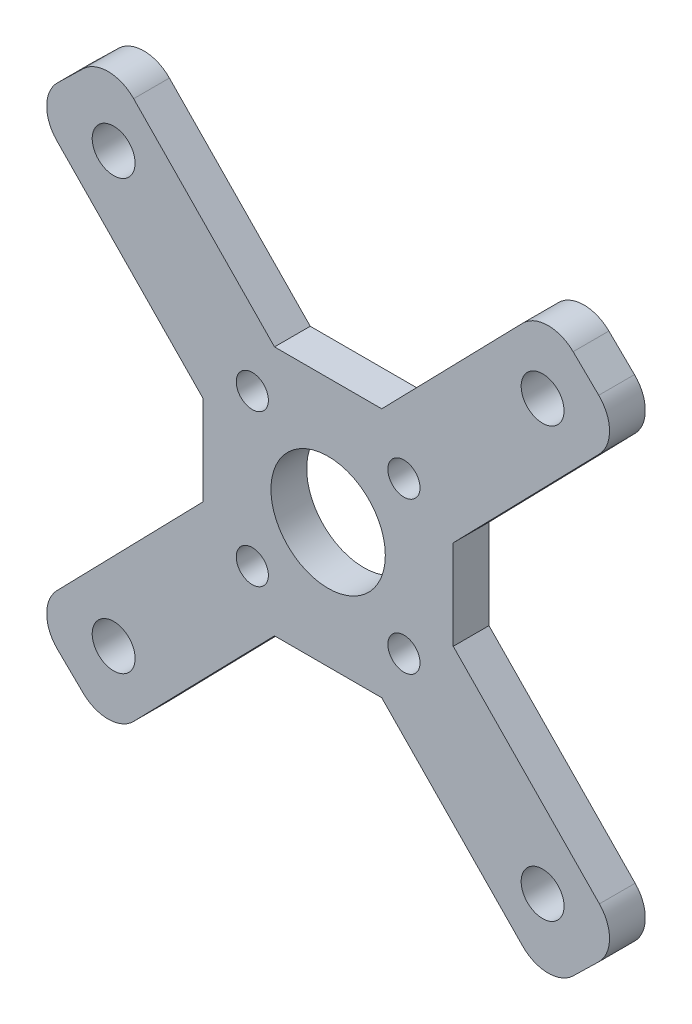
SolidWorks part; units mm, degrees
ref_plane "Plan de face" through (0, 0, 0) normal (0, 0, 1) x (1, 0, 0)
ref_plane "Plan de dessus" through (0, 0, 0) normal (0, 1, 0) x (1, 0, 0)
ref_plane "Plan de droite" through (0, 0, 0) normal (1, 0, 0) x (0, 0, -1)
sketch "Esquisse1" plane through (0, 0, 0) normal (0, 0, 1) x (1, 0, 0)
  line L0 (-10.605, 10.605) -> (-10.605, -10.605) construction
  line L1 (7.5, -17.5) -> (-7.5, -17.5)
  line L2 (17.5, -7.5) -> (17.5, 7.5)
  line L3 (7.5, 17.5) -> (-7.5, 17.5)
  line L4 (-17.5, -7.5) -> (-17.5, 7.5)
  line L5 (17.5, -17.5) -> (-17.5, 17.5) construction
  line L6 (17.5, 17.5) -> (-17.5, -17.5) construction
  line L7 (-10.605, 10.605) -> (10.605, 10.605) construction
  line L8 (10.605, 10.605) -> (10.605, -10.605) construction
  circle A0 centre (0, 0) radius 8
  circle A1 centre (-10.605, 10.605) radius 2.25
  circle A2 centre (10.605, 10.605) radius 2.25
  circle A3 centre (-10.605, -10.605) radius 2.25
  circle A4 centre (10.605, -10.605) radius 2.25
  arc A5 (-7.5, -17.5) -> (-17.5, -7.5) centre (-7.5, -7.5) cw
  arc A6 (7.5, -17.5) -> (17.5, -7.5) centre (7.5, -7.5) ccw
  arc A7 (17.5, 7.5) -> (7.5, 17.5) centre (7.5, 7.5) ccw
  arc A8 (-7.5, 17.5) -> (-17.5, 7.5) centre (-7.5, 7.5) ccw
  point P0 (0, 0)
  point P16 (0, 0)
  point P17 (8.9507, -11.9448)
  point P18 (10.605, 0)
  point P19 (0, 10.605)
  point P20 (-10.605, 0)
  point P21 (0, 0)
  point P22 (9.4172, 10.605)
  dimension "D1" = 4.5
  dimension "D2" = 4.5
  dimension "D3" = 4.5
  dimension "D4" = 4.5
  dimension "D7" = 16
  dimension "D10" = 10
  dimension "D5" = 21.21
  dimension "D6" = 21.21
  dimension "D8" = 35
  dimension "D9" = 35
extrude "Boss.-Extru.1" add sketch "Esquisse1" along normal blind 5
sketch "Esquisse2" plane through (0, 0, 5) normal (0, 0, 1) x (1, 0, 0)
  line L0 (-38.0784, 38.0784) -> (30.6138, -30.6138) construction
  line L1 (37.8813, 37.8813) -> (-34.8497, -34.8497) construction
  line L2 (-17.4124, 6.1793) -> (-37.9445, 27.2476)
  line L3 (-37.8534, 34.3181) -> (-34.2726, 37.8078)
  line L4 (-27.2021, 37.7167) -> (-7.5, 17.5)
  line L5 (-30, 30) -> (-42.1259, 42.1259) construction
  line L6 (0, 38.0784) -> (0, -34.8497) construction
  line L7 (-51.3686, 0) -> (60.5572, 0) construction
  line L8 (37.8534, 34.3181) -> (34.2726, 37.8078)
  line L9 (17.4124, 6.1793) -> (37.9445, 27.2476)
  line L10 (27.2021, 37.7167) -> (7.5, 17.5)
  line L11 (17.4124, -6.1793) -> (37.9445, -27.2476)
  line L12 (27.2021, -37.7167) -> (7.5, -17.5)
  line L13 (37.8534, -34.3181) -> (34.2726, -37.8078)
  line L14 (-37.8534, -34.3181) -> (-34.2726, -37.8078)
  line L15 (-17.4124, -6.1793) -> (-37.9445, -27.2476)
  line L16 (-27.2021, -37.7167) -> (-7.5, -17.5)
  circle A0 centre (-10.605, -10.605) radius 2.25 construction
  circle A1 centre (10.605, -10.605) radius 2.25 construction
  circle A2 centre (10.605, 10.605) radius 2.25 construction
  circle A3 centre (-10.605, 10.605) radius 2.25 construction
  circle A4 centre (-10.605, -10.605) radius 2.25
  circle A5 centre (10.605, -10.605) radius 2.25
  circle A6 centre (10.605, 10.605) radius 2.25
  circle A7 centre (-10.605, 10.605) radius 2.25
  circle A8 centre (-30, 30) radius 3
  circle A9 centre (30, 30) radius 3
  circle A10 centre (-30, -30) radius 3
  circle A11 centre (30, -30) radius 3
  arc A12 (-7.5, 17.5) -> (-17.5, 7.5) centre (-7.5, 7.5) ccw construction
  arc A13 (-7.5, 17.5) -> (-17.4124, 6.1793) centre (-7.5, 7.5) ccw
  arc A14 (7.5, 17.5) -> (17.4124, 6.1793) centre (7.5, 7.5) cw
  arc A15 (7.5, -17.5) -> (17.4124, -6.1793) centre (7.5, -7.5) ccw
  arc A16 (-7.5, -17.5) -> (-17.4124, -6.1793) centre (-7.5, -7.5) cw
  arc A17 (-37.8534, -34.3181) -> (-37.9445, -27.2476) centre (-34.3637, -30.7373) cw
  arc A18 (-34.2726, -37.8078) -> (-27.2021, -37.7167) centre (-30.7829, -34.227) ccw
  arc A19 (27.2021, -37.7167) -> (34.2726, -37.8078) centre (30.7829, -34.227) ccw
  arc A20 (37.9445, -27.2476) -> (37.8534, -34.3181) centre (34.3637, -30.7373) cw
  arc A21 (37.8534, 34.3181) -> (37.9445, 27.2476) centre (34.3637, 30.7373) cw
  arc A22 (34.2726, 37.8078) -> (27.2021, 37.7167) centre (30.7829, 34.227) ccw
  arc A23 (-34.2726, 37.8078) -> (-27.2021, 37.7167) centre (-30.7829, 34.227) cw
  arc A24 (-37.9445, 27.2476) -> (-37.8534, 34.3181) centre (-34.3637, 30.7373) cw
  point P30 (-36.063, 36.063)
  point P37 (-8.4349, 17.4562)
  point P39 (-41.192, 30.5918)
  point P40 (-6.7466, 17.4716)
  point P41 (0, 0)
  point P59 (-41.4342, -30.8285)
  point P62 (-30.6917, -41.2975)
  point P65 (30.6917, -41.2975)
  point P68 (41.4342, -30.8285)
  point P71 (41.4342, 30.8285)
  point P74 (30.6917, 41.2975)
  point P77 (-30.6917, 41.2975)
  point P80 (-41.4342, 30.8285)
  arc M26 (-17.5, -7.5) -> (-7.5, -17.5) centre (-7.5, -7.5) ccw
  arc M28 (7.5, -17.5) -> (17.5, -7.5) centre (7.5, -7.5) ccw
  line M29 (17.5, -7.5) -> (17.5, 7.5)
  arc M30 (17.5, 7.5) -> (7.5, 17.5) centre (7.5, 7.5) ccw
  arc M32 (-7.5, 17.5) -> (-17.5, 7.5) centre (-7.5, 7.5) ccw
  line M33 (-17.5, 7.5) -> (-17.5, -7.5)
  dimension "D2" = 6
  dimension "D5" = 5
  dimension "D1" = 30
  dimension "D3" = 15
  dimension "D4" = 36
extrude "Boss.-Extru.2" add sketch "Esquisse2" against normal blind 5 contours A24 L2 L4 A23 L3 A8 M33 M32 | L8 A22 L10 L9 A21 A9 M30 M29 | A20 L11 L12 A19 L13 A11 M29 M28 | L14 A18 L16 L15 A17 A10 M26 M33
